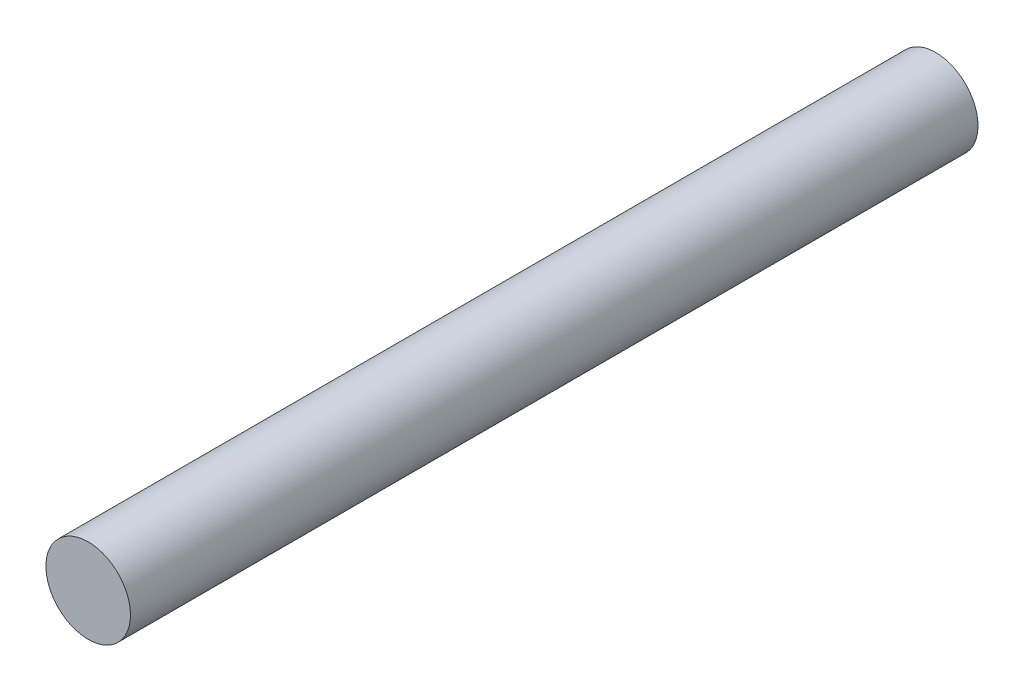
SolidWorks part; units mm, degrees
ref_plane "Front Plane" through (0, 0, 0) normal (0, 0, 1) x (1, 0, 0)
ref_plane "Top Plane" through (0, 0, 0) normal (0, 1, 0) x (1, 0, 0)
ref_plane "Right Plane" through (0, 0, 0) normal (1, 0, 0) x (0, 0, -1)
sketch "Sketch1" plane through (0, 0, 0) normal (0, 0, 1) x (1, 0, 0)
  circle A0 centre (0, 0) radius 4.075
  dimension "D1" = 8.15
extrude "Boss-Extrude1" add sketch "Sketch1" against normal blind 81.7
